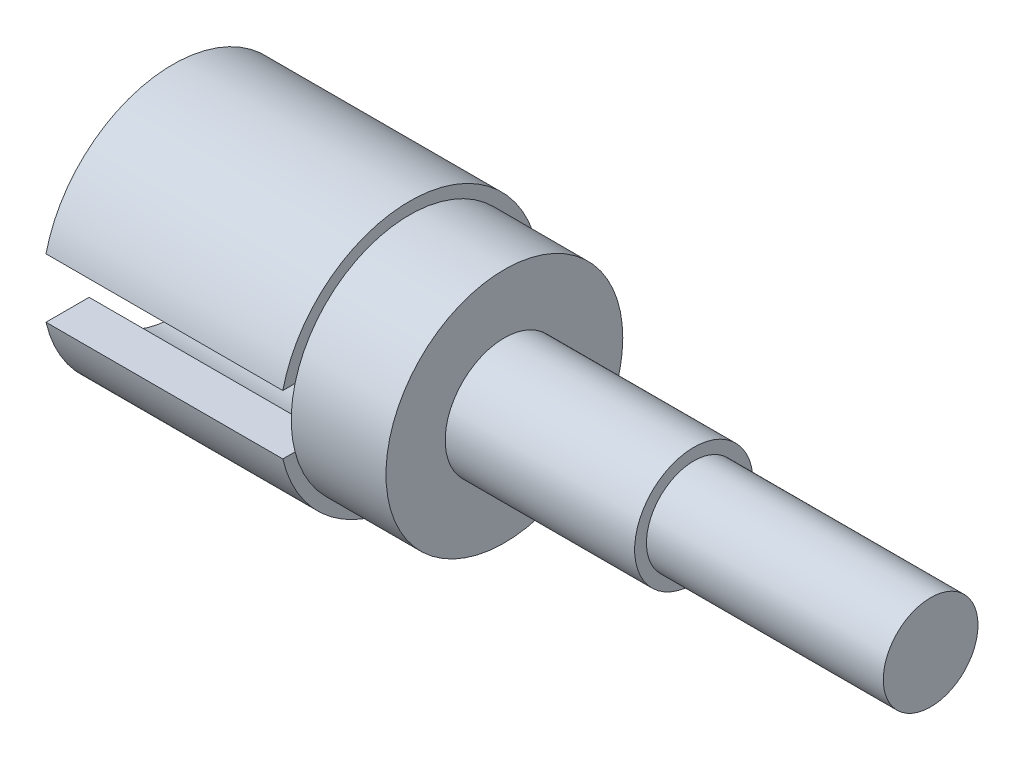
SolidWorks part; units mm, degrees
material "AISI 304"
ref_plane "Front" through (0, 0, 0) normal (0, 0, 1) x (1, 0, 0)
ref_plane "Top" through (0, 0, 0) normal (0, 1, 0) x (1, 0, 0)
ref_plane "Right" through (0, 0, 0) normal (1, 0, 0) x (0, 0, -1)
sketch "Sketch1" plane through (0, 0, 0) normal (1, 0, 0) x (0, 0, -1)
  circle A0 centre (0, 0) radius 5.5
  dimension "D1" = 11
extrude "Boss-Extrude1" add sketch "Sketch1" along normal blind 10
sketch "Sketch2" plane through (10, 0, 0) normal (1, 0, 0) x (0, 0, -1)
  circle A0 centre (0, 0) radius 5
  dimension "D1" = 10
extrude "Boss-Extrude2" add sketch "Sketch2" along normal blind 4
sketch "Sketch3" plane through (14, 0, 0) normal (1, 0, 0) x (0, 0, -1)
  circle A0 centre (0, 0) radius 2.5
  point P3 (0, 0)
  dimension "D1" = 5
extrude "Boss-Extrude3" add sketch "Sketch3" along normal blind 8
sketch "Sketch4" plane through (22, 0, 0) normal (1, 0, 0) x (0, 0, -1)
  circle A0 centre (0, 0) radius 2
  dimension "D1" = 4
extrude "Boss-Extrude4" add sketch "Sketch4" along normal blind 10
sketch "Sketch5" plane through (0, 0, 0) normal (-1, 0, 0) x (0, 0, 1)
  circle A0 centre (0, 0) radius 3.75
  dimension "D1" = 7.5
extrude "Cut-Extrude1" cut sketch "Sketch5" against normal blind 9
sketch "Sketch6" plane through (0, 0, 0) normal (-1, 0, 0) x (0, 0, 1)
  line L1 (-11.0703, -1.25) -> (14.4371, -1.25)
  line L2 (-11.0703, -1.25) -> (-11.0703, 1.25)
  line L3 (-11.0703, 1.25) -> (14.4371, 1.25)
  line L4 (14.4371, -1.25) -> (14.4371, 1.25)
  circle A1 centre (0, 0) radius 5.5 construction
  dimension "D1" = 2.5
  dimension "D2" = 1.25
extrude "Cut-Extrude2" cut sketch "Sketch6" against normal blind 10
